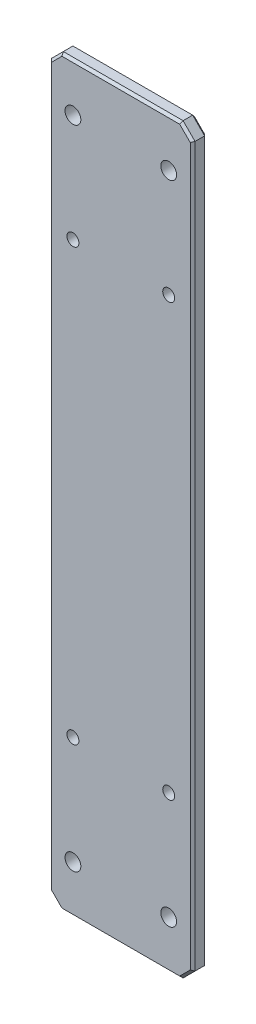
SolidWorks part; units mm, degrees
ref_plane "前视基准面" through (0, 0, 0) normal (0, 0, 1) x (1, 0, 0)
ref_plane "上视基准面" through (0, 0, 0) normal (0, 1, 0) x (1, 0, 0)
ref_plane "右视基准面" through (0, 0, 0) normal (1, 0, 0) x (0, 0, -1)
sketch "草图1" plane through (0, 0, 0) normal (0, 0, 1) x (1, 0, 0)
  line L1 (-30, 155) -> (30, 155)
  line L2 (-30, 155) -> (-30, -155)
  line L3 (-30, -155) -> (30, -155)
  line L4 (30, 155) -> (30, -155)
  line L5 (-30, 155) -> (30, -155) construction
  line L6 (-30, -155) -> (30, 155) construction
  point P0 (0, 0)
  dimension "D1" = 60
  dimension "D2" = 310
extrude "凸台-拉伸1" add sketch "草图1" along normal blind 6
sketch "草图2" plane through (0, 0, 6) normal (0, 0, 1) x (1, 0, 0)
  line L0 (30, 155) -> (-30, 155) construction
  line L1 (-20, -135) -> (20, -135) construction
  line L2 (-20, -135) -> (-20, 135) construction
  line L3 (-20, 135) -> (20, 135) construction
  line L4 (20, -135) -> (20, 135) construction
  line L5 (-20, -135) -> (20, 135) construction
  line L6 (-20, 135) -> (20, -135) construction
  circle A0 centre (-20, 135) radius 3.3
  circle A1 centre (20, 135) radius 3.3
  circle A2 centre (-20, -135) radius 3.3
  circle A3 centre (20, -135) radius 3.3
  point P0 (0, 0)
  dimension "D3" = 6.6
  dimension "D1" = 40
  dimension "D2" = 20
extrude "切除-拉伸1" cut sketch "草图2" against normal through all
chamfer "倒角2" distance 5 angle 45 4 edges at (-30, -155, 3) (30, -155, 3) (-30, 155, 3) (30, 155, 3)
chamfer "倒角1" distance 1 angle 45 16 edges at (-30, 0, 6) (-27.5, -152.5, 6) (-27.5, 152.5, 6) (0, -155, 6) (0, 155, 6) (27.5, -152.5, 6) (27.5, 152.5, 6) (30, 0, 6) (-30, 0, 0) (-27.5, -152.5, 0) (-27.5, 152.5, 0) (0, -155, 0) (0, 155, 0) (27.5, -152.5, 0) (27.5, 152.5, 0) (30, 0, 0)
hole_wizard "M6 螺纹孔1" positions "草图3" profile "草图4" tap size "M6" standard "GB"
sketch "草图3" plane through (0, 0, 0) normal (0, 0, -1) x (-1, 0, 0)
  point P0 (-20, 90)
  point P3 (20, 90)
  point P6 (20, -90)
  point P9 (-20, -90)
sketch "草图4" plane through (20, 90, 0) normal (1, 0, 0) x (0, 1, 0)
  line L0 (0, 0) -> (0, 21.2522)
  line L1 (0, 21.2522) -> (2.5, 19.75)
  line L2 (2.5, 19.75) -> (2.5, 0)
  line L5 (2.5, 0) -> (0, 0)
  line L10 (0, 21.2522) -> (-2.5, 19.75) construction
  line L11 (0, -6.35) -> (0, 107.95) construction
  dimension "螺纹孔钻头直径" = 5
  dimension "螺纹孔钻头深度" = 19.75
  dimension "导头角度" = 118
cosmetic thread "孔螺蚊线1" parameters "D1"=12, "D2"=6
cosmetic thread "孔螺蚊线2" parameters "D1"=12, "D2"=6
cosmetic thread "孔螺蚊线3" parameters "D1"=12, "D2"=6
cosmetic thread "孔螺蚊线4" parameters "D1"=12, "D2"=6
